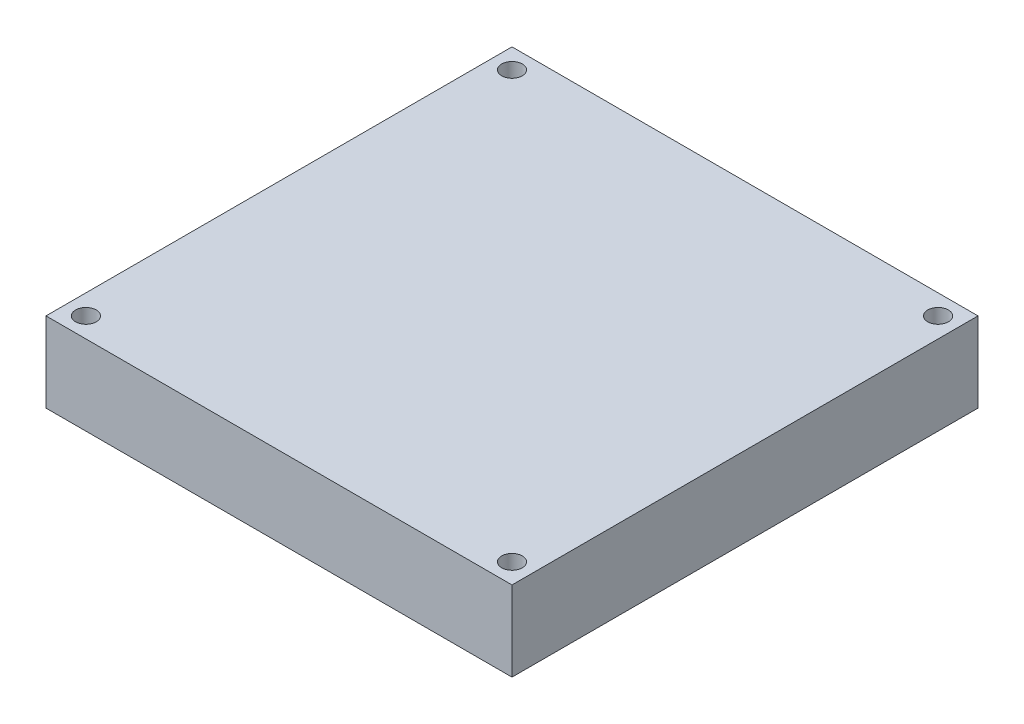
SolidWorks part; units mm, degrees
ref_plane "Plano frontal" through (0, 0, 0) normal (0, 0, 1) x (1, 0, 0)
ref_plane "Plano superior" through (0, 0, 0) normal (0, 1, 0) x (1, 0, 0)
ref_plane "Plano direito" through (0, 0, 0) normal (1, 0, 0) x (0, 0, -1)
sketch "Esboço1" plane through (0, 0, 0) normal (0, 1, 0) x (1, 0, 0)
  line L1 (-35, -35) -> (35, -35)
  line L2 (-35, -35) -> (-35, 35)
  line L3 (-35, 35) -> (35, 35)
  line L4 (35, -35) -> (35, 35)
  line L5 (-35, -35) -> (35, 35) construction
  line L6 (-35, 35) -> (35, -35) construction
  point P0 (0, 0)
  dimension "D1" = 70
extrude "Ressalto-extrusão1" add sketch "Esboço1" along normal blind 12
sketch "Esboço2" plane through (0, 12, 0) normal (0, 1, 0) x (1, 0, 0)
  line L0 (35, 35) -> (-35, 35) construction
  line L1 (-35, 35) -> (-35, -35) construction
  line L2 (0, 0) -> (0, 11.2358) construction
  line L3 (0, 0) -> (12.0171, 0) construction
  circle A0 centre (-32, 32) radius 1.55
  circle A1 centre (32, 32) radius 1.55
  circle A2 centre (32, -32) radius 1.55
  circle A3 centre (-32, -32) radius 1.55
  dimension "D3" = 3.1
  dimension "D1" = 3
  dimension "D2" = 3
extrude "Corte-extrusão1" cut sketch "Esboço2" against normal up to surface (12 mm away) up to face at (0, 0, 0)
equation "\"D2@Esboço2\"=\"D1@Esboço2\""
